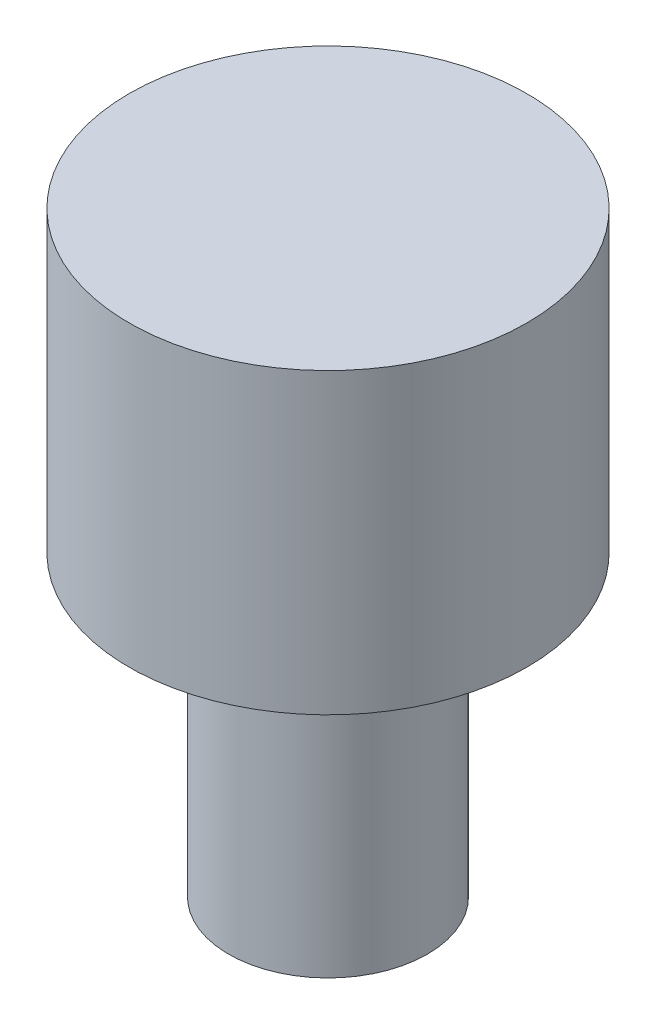
SolidWorks part; units mm, degrees
ref_plane "Front Plane" through (0, 0, 0) normal (0, 0, 1) x (1, 0, 0)
ref_plane "Top Plane" through (0, 0, 0) normal (0, 1, 0) x (1, 0, 0)
ref_plane "Right Plane" through (0, 0, 0) normal (1, 0, 0) x (0, 0, -1)
sketch "Sketch1" plane through (0, 0, 0) normal (0, 0, 1) x (1, 0, 0)
  line L1 (0, 30) -> (-20, 30)
  line L2 (-20, 0) -> (-20, 30)
  line L3 (-20, 0) -> (-10, 0)
  line L4 (-10, 0) -> (-10, -30)
  line L5 (-10, -30) -> (0, -30)
  line L6 (0, -30) -> (0, 30)
  point P0 (0, -44.7429)
  dimension "D1" = 30
  dimension "20" = 20
  dimension "D2" = 30
  dimension "D3" = 10
revolve "Revolve1" add sketch "Sketch1" angle 360 about L6
